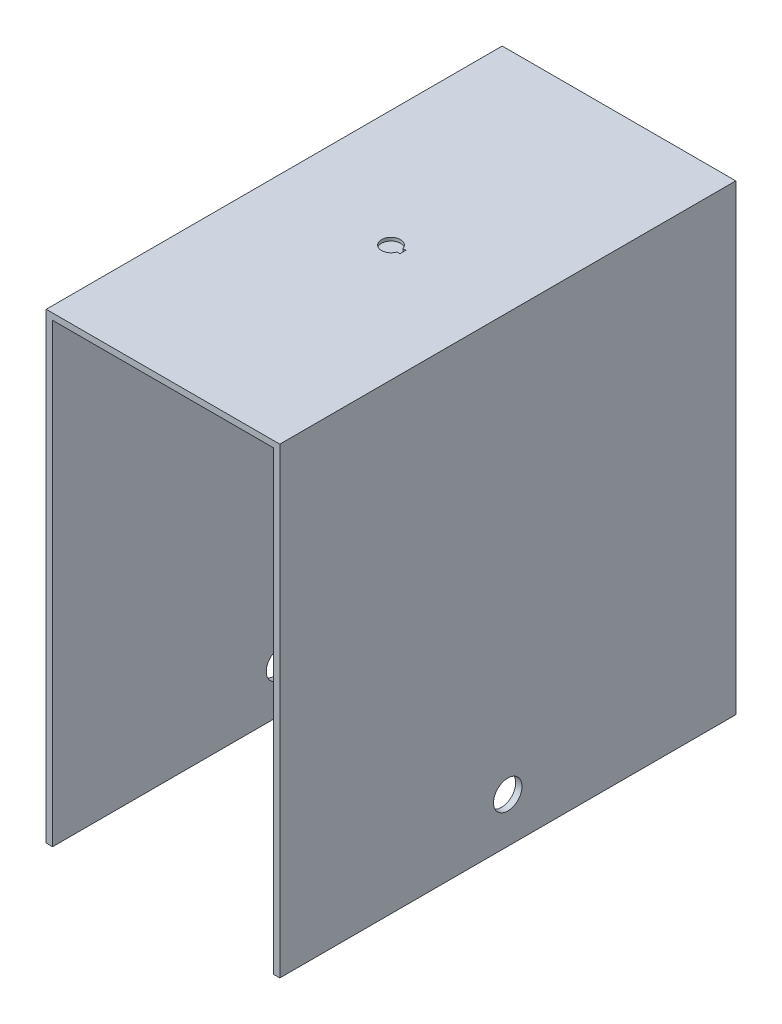
SolidWorks part; units mm, degrees
ref_plane "Front Plane" through (0, 0, 0) normal (0, 0, 1) x (1, 0, 0)
ref_plane "Top Plane" through (0, 0, 0) normal (0, 1, 0) x (1, 0, 0)
ref_plane "Right Plane" through (0, 0, 0) normal (1, 0, 0) x (0, 0, -1)
sketch "Sketch1" plane through (0, 0, 0) normal (0, 1, 0) x (1, 0, 0)
  line L1 (-117.095, -228.6) -> (117.095, -228.6)
  line L2 (-117.095, -228.6) -> (-117.095, 228.6)
  line L3 (-117.095, 228.6) -> (117.095, 228.6)
  line L4 (117.095, -228.6) -> (117.095, 228.6)
  line L5 (-117.095, -228.6) -> (117.095, 228.6) construction
  line L6 (-117.095, 228.6) -> (117.095, -228.6) construction
  point P0 (0, 0)
  dimension "D1" = 234.19
  dimension "D2" = 457.2
extrude "Boss-Extrude1" add sketch "Sketch1" against normal blind 6.35
sketch "Sketch2" plane through (0, -6.35, 0) normal (0, -1, 0) x (1, 0, 0)
  line L0 (117.095, -228.6) -> (-117.095, -228.6) construction
  line L1 (-117.095, 228.6) -> (-110.745, 228.6)
  line L2 (-117.095, 228.6) -> (-117.095, -228.6)
  line L3 (-117.095, -228.6) -> (-110.745, -228.6)
  line L4 (-110.745, 228.6) -> (-110.745, -228.6)
  dimension "D1" = 6.35
extrude "Boss-Extrude2" add sketch "Sketch2" along normal blind 457.2
mirror "Mirror1" about plane through (0, 0, 0) normal (1, 0, 0) of "Boss-Extrude2"
sketch "Sketch3" plane through (117.095, 0, 0) normal (1, 0, 0) x (0, 0, -1)
  line L0 (0, 0) -> (0, -463.55) construction
  line L1 (-228.6, 0) -> (228.6, 0) construction
  line L2 (-228.6, -463.55) -> (228.6, -463.55) construction
  line L3 (-228.6, -418.55) -> (228.6, -418.55) construction
  line L4 (-228.6, -463.55) -> (-228.6, 0) construction
  line L5 (228.6, -463.55) -> (228.6, 0) construction
  circle A0 centre (0, -418.55) radius 14.29
  dimension "D2" = 28.58
  dimension "D1" = 45
extrude "Cut-Extrude1" cut sketch "Sketch3" against normal blind 558.8
sketch "Sketch4" plane through (0, 0, 0) normal (0, 1, 0) x (1, 0, 0)
  line L0 (0, 228.6) -> (0, -228.6) construction
  line L1 (117.095, 228.6) -> (-117.095, 228.6) construction
  line L2 (-117.095, -228.6) -> (117.095, -228.6) construction
  line L4 (9.0139, 3) -> (12, 3)
  line L6 (9.0139, -3) -> (12, -3)
  line L7 (12, 3) -> (12, -3)
  line L8 (7, 3) -> (12, -3) construction
  line L9 (7, -3) -> (12, 3) construction
  arc A0 (9.0139, 3) -> (9.0139, -3) centre (0, 0) ccw
  point P9 (9.5, 0)
  dimension "D1" = 19
  dimension "D2" = 6
  dimension "D3" = 12
  dimension "D4" = 9.0139
extrude "Cut-Extrude2" cut sketch "Sketch4" against normal blind 3.25
